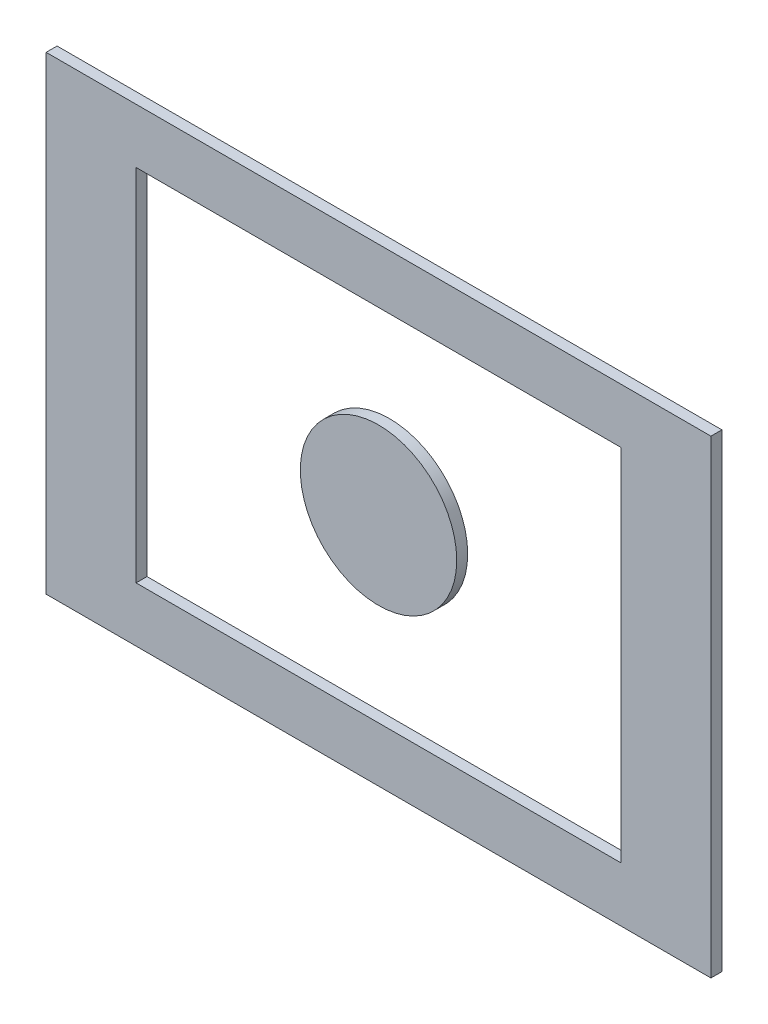
SolidWorks part; units mm, degrees
ref_plane "前视基准面" through (0, 0, 0) normal (0, 0, 1) x (1, 0, 0)
ref_plane "上视基准面" through (0, 0, 0) normal (0, 1, 0) x (1, 0, 0)
ref_plane "右视基准面" through (0, 0, 0) normal (1, 0, 0) x (0, 0, -1)
sketch "草图1" plane through (0, 0, 0) normal (0, 0, 1) x (1, 0, 0)
  line L1 (-42.5, 30) -> (42.5, 30)
  line L2 (-42.5, 30) -> (-42.5, -30)
  line L3 (-42.5, -30) -> (42.5, -30)
  line L4 (42.5, 30) -> (42.5, -30)
  line L5 (-42.5, 30) -> (42.5, -30) construction
  line L6 (-42.5, -30) -> (42.5, 30) construction
  line L7 (-31, 23) -> (31, 23)
  line L8 (-31, 23) -> (-31, -23)
  line L9 (-31, -23) -> (31, -23)
  line L10 (31, 23) -> (31, -23)
  line L11 (-31, 23) -> (31, -23) construction
  line L12 (-31, -23) -> (31, 23) construction
  point P0 (0, 0)
  point P6 (0, 0)
  dimension "D1" = 85
  dimension "D2" = 60
  dimension "D3" = 7
  dimension "D4" = 11.5
extrude "凸台-拉伸1" add sketch "草图1" along normal blind 1.4
sketch "草图2" plane through (0, 0, 1.4) normal (0, 0, 1) x (1, 0, 0)
  circle A0 centre (0, 0) radius 10
  dimension "D1" = 20
extrude "凸台-拉伸2" add sketch "草图2" against normal blind 1.4 separate body
